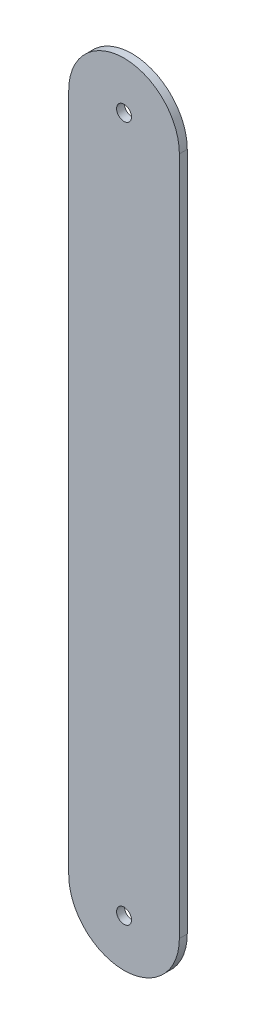
SolidWorks part; units mm, degrees
ref_plane "Front Plane" through (0, 0, 0) normal (0, 0, 1) x (1, 0, 0)
ref_plane "Top Plane" through (0, 0, 0) normal (0, 1, 0) x (1, 0, 0)
ref_plane "Right Plane" through (0, 0, 0) normal (1, 0, 0) x (0, 0, -1)
sketch "Sketch1" plane through (0, 0, 0) normal (0, 0, 1) x (1, 0, 0)
  line L0 (0, 68.2625) -> (0, -68.2625) construction
  line L1 (-11.1125, 68.2625) -> (11.1125, 68.2625)
  line L2 (-11.1125, 68.2625) -> (-11.1125, -68.2625)
  line L3 (-11.1125, -68.2625) -> (11.1125, -68.2625)
  line L4 (11.1125, 68.2625) -> (11.1125, -68.2625)
  arc A0 (-11.1125, 68.2625) -> (11.1125, 68.2625) centre (0, 68.2625) cw
  arc A1 (-11.1125, -68.2625) -> (11.1125, -68.2625) centre (0, -68.2625) ccw
  circle A2 centre (0, -69.85) radius 1.5
  circle A3 centre (0, 69.85) radius 1.5
  point P10 (0, 79.375)
  point P11 (0, -79.375)
  point P14 (0, 0)
  dimension "D2" = 139.7
  dimension "D5" = 3
  dimension "D6" = 3
  dimension "D1" = 22.225
  dimension "D3" = 9.525
  dimension "D4" = 9.525
extrude "Boss-Extrude1" add sketch "Sketch1" along normal blind 1.5875 contours A0 L1 A3 | L1 L0 L3 L4 | L0 L1 L2 L3 | L3 A1 A2
